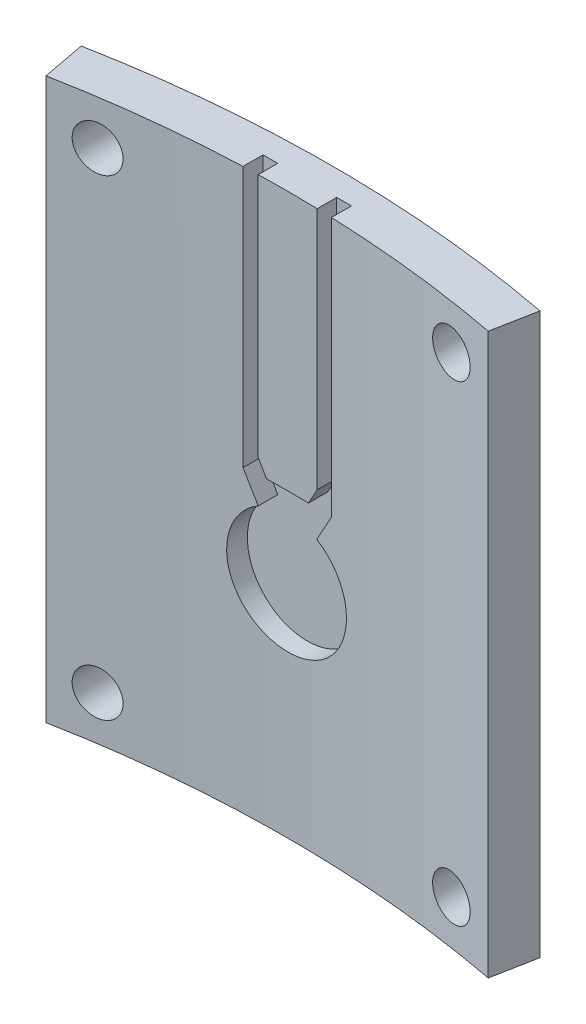
SolidWorks part; units mm, degrees
ref_plane "Front Plane" through (0, 0, 0) normal (0, 0, 1) x (1, 0, 0)
ref_plane "Top Plane" through (0, 0, 0) normal (0, 1, 0) x (1, 0, 0)
ref_plane "Right Plane" through (0, 0, 0) normal (1, 0, 0) x (0, 0, -1)
sketch "Sketch1" plane through (0, 0, 0) normal (0, 1, 0) x (1, 0, 0)
  line L0 (0, 101.6) -> (0, 0) construction
  line L1 (-19.05, 99.7981) -> (19.05, 99.7981) construction
  line L2 (-19.05, 99.7981) -> (-19.7644, 103.5405)
  line L3 (19.05, 99.7981) -> (19.7644, 103.5405)
  line L4 (19.05, 99.7981) -> (0, 0) construction
  arc A0 (-19.05, 99.7981) -> (19.05, 99.7981) centre (0, 0) cw
  arc A1 (-19.7644, 103.5405) -> (19.7644, 103.5405) centre (0, 0) cw
  dimension "D1" = 101.6
  dimension "D2" = 19.05
  dimension "D3" = 3.81
extrude "Boss-Extrude1" add sketch "Sketch1" along normal blind 48.26
sketch "Sketch2" plane through (0, 0, 0) normal (0, 0, 1) x (1, 0, 0)
  line L0 (-2.54, 23.5408) -> (-3.81, 25.7862)
  line L1 (-3.81, 25.7862) -> (-3.81, 48.26)
  line L2 (19.05, 48.26) -> (-19.05, 48.26) construction
  line L3 (-3.81, 48.26) -> (-2.54, 48.26)
  line L4 (-2.54, 48.26) -> (-2.54, 27.1524)
  line L5 (-2.54, 27.1524) -> (-1.8362, 25.908)
  line L6 (-1.8362, 25.908) -> (1.776, 25.908)
  line L7 (1.776, 25.908) -> (2.54, 27.2831)
  line L8 (2.54, 27.2831) -> (2.54, 48.26)
  line L9 (2.54, 48.26) -> (3.81, 48.26)
  line L10 (3.81, 48.26) -> (3.81, 25.908)
  line L11 (3.81, 25.908) -> (2.5056, 23.5601)
  line L12 (0, 19.05) -> (0, 48.26) construction
  arc A0 (-2.54, 23.5408) -> (2.5056, 23.5601) centre (0, 19.05) ccw
  point P8 (0, 19.05)
  dimension "D1" = 10.3187
  dimension "D2" = 2.54
  dimension "D3" = 1.27
  dimension "D4" = 2.54
  dimension "D5" = 1.27
  dimension "D6" = 6.858
  dimension "D7" = 19.05
  dimension "D8" = 1.778
  dimension "D9" = 1.778
extrude "Cut-Extrude1" cut sketch "Sketch2" against normal blind 103.251
sketch "Sketch3" plane through (0, 0, 0) normal (0, 0, 1) x (1, 0, 0)
  line L0 (-3.81, 48.26) -> (-19.05, 48.26) construction
  line L1 (-19.05, 48.26) -> (-19.05, 0) construction
  line L2 (19.05, 48.26) -> (3.81, 48.26) construction
  line L3 (19.05, 48.26) -> (19.05, 0) construction
  line L4 (-19.05, 0) -> (19.05, 0) construction
  circle A0 centre (-15.24, 44.45) radius 1.905
  circle A1 centre (15.24, 44.45) radius 1.905
  circle A2 centre (-15.24, 3.81) radius 1.905
  circle A3 centre (15.24, 3.81) radius 1.905
  dimension "D1" = 3.81
  dimension "D2" = 3.81
  dimension "D3" = 3.81
  dimension "D4" = 3.81
  dimension "D5" = 3.81
  dimension "D6" = 3.81
  dimension "D7" = 3.81
  dimension "D8" = 3.81
  dimension "D9" = 3.81
extrude "Cut-Extrude2" cut sketch "Sketch3" against normal through all
